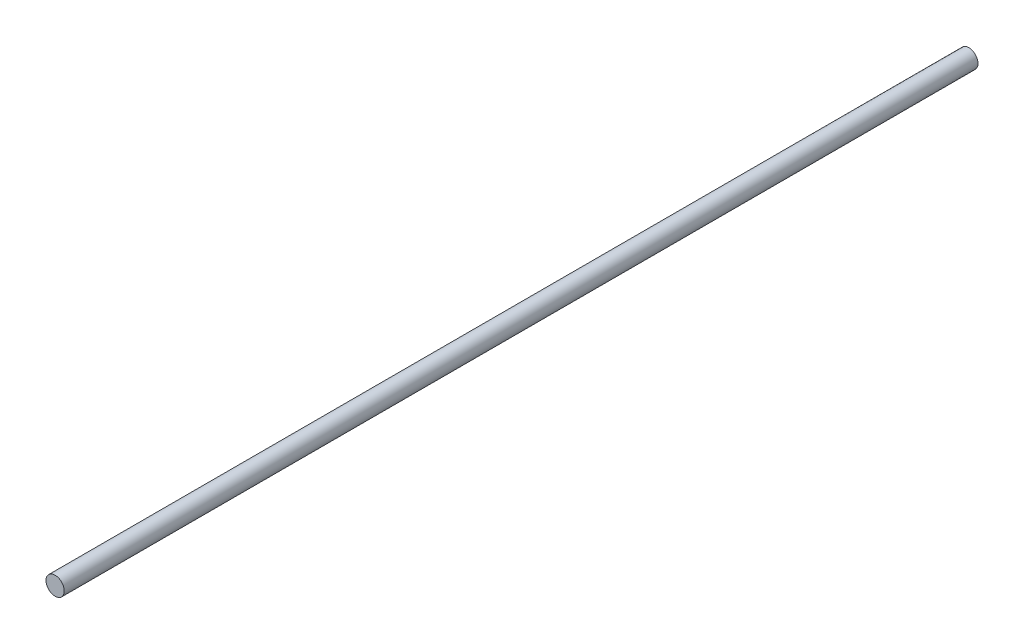
SolidWorks part; units mm, degrees
ref_plane "正面" through (0, 0, 0) normal (0, 0, 1) x (1, 0, 0)
ref_plane "平面" through (0, 0, 0) normal (0, 1, 0) x (1, 0, 0)
ref_plane "右側面" through (0, 0, 0) normal (1, 0, 0) x (0, 0, -1)
sketch "ｽｹｯﾁ1" plane through (0, 0, 0) normal (0, 0, 1) x (1, 0, 0)
  circle A0 centre (0, 0) radius 1
  dimension "D1" = 2
extrude "ﾎﾞｽ - 押し出し1" add sketch "ｽｹｯﾁ1" along normal blind 100 contours A0
